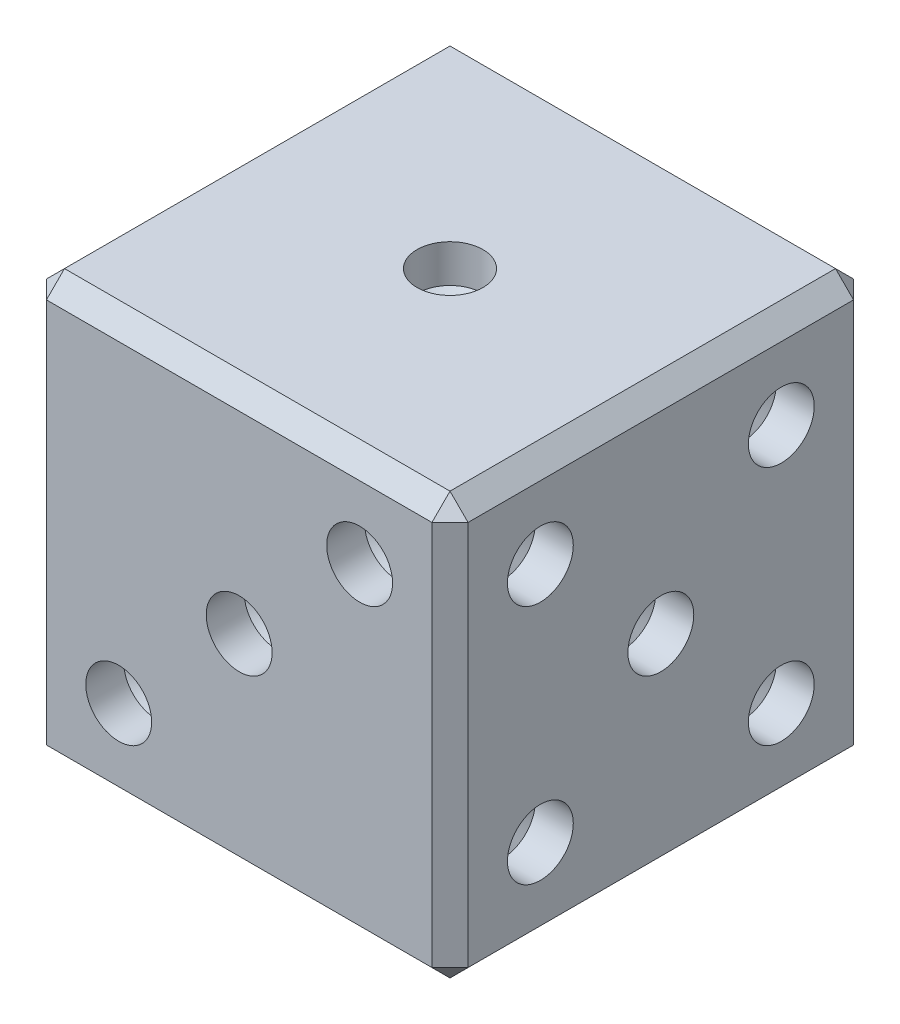
SolidWorks part; units mm, degrees
ref_plane "Front Plane" through (0, 0, 0) normal (0, 0, 1) x (1, 0, 0)
ref_plane "Top Plane" through (0, 0, 0) normal (0, 1, 0) x (1, 0, 0)
ref_plane "Right Plane" through (0, 0, 0) normal (1, 0, 0) x (0, 0, -1)
sketch "Sketch1" plane through (0, 0, 0) normal (0, 1, 0) x (1, 0, 0)
  line L1 (-8.89, -8.89) -> (8.89, -8.89)
  line L2 (-8.89, -8.89) -> (-8.89, 8.89)
  line L3 (-8.89, 8.89) -> (8.89, 8.89)
  line L4 (8.89, -8.89) -> (8.89, 8.89)
  line L5 (-8.89, -8.89) -> (8.89, 8.89) construction
  line L6 (-8.89, 8.89) -> (8.89, -8.89) construction
  point P0 (0, 0)
  dimension "D1" = 17.78
  dimension "D2" = 17.78
extrude "Boss-Extrude1" add sketch "Sketch1" along normal mid plane 17.78 contours L2 L1 L4 L3
sketch "Sketch2" plane through (0, 0, 0) normal (0, 0, 1) x (1, 0, 0)
  line L5 (-5.08, -5.08) -> (5.08, -5.08)
  line L6 (-5.08, -5.08) -> (-5.08, 5.08)
  line L7 (-5.08, 5.08) -> (5.08, 5.08)
  line L8 (5.08, -5.08) -> (5.08, 5.08)
  line L9 (-5.08, -5.08) -> (5.08, 5.08) construction
  line L10 (-5.08, 5.08) -> (5.08, -5.08) construction
  point P0 (0, 0)
  point P5 (0, 0)
  dimension "D1" = 10.16
  dimension "D2" = 10.16
sketch "Sketch3" plane through (0, 0, 0) normal (0, 1, 0) x (1, 0, 0)
  line L5 (-5.08, -5.08) -> (5.08, -5.08)
  line L6 (-5.08, -5.08) -> (-5.08, 5.08)
  line L7 (-5.08, 5.08) -> (5.08, 5.08)
  line L8 (5.08, -5.08) -> (5.08, 5.08)
  line L9 (-5.08, -5.08) -> (5.08, 5.08) construction
  line L10 (-5.08, 5.08) -> (5.08, -5.08) construction
  point P0 (0, 0)
  dimension "D1" = 10.16
  dimension "D2" = 10.16
sketch "Sketch4" plane through (0, 0, 0) normal (1, 0, 0) x (0, 0, -1)
  line L5 (-5.08, -5.08) -> (5.08, -5.08)
  line L6 (-5.08, -5.08) -> (-5.08, 5.08)
  line L7 (-5.08, 5.08) -> (5.08, 5.08)
  line L8 (5.08, -5.08) -> (5.08, 5.08)
  line L9 (-5.08, -5.08) -> (5.08, 5.08) construction
  line L10 (-5.08, 5.08) -> (5.08, -5.08) construction
  point P0 (0, 0)
  dimension "D1" = 10.16
  dimension "D2" = 10.16
chamfer "Chamfer1" distance 0.762 angle 45 12 edges at (-8.89, 0, -8.89) (0, 8.89, -8.89) (-8.89, 8.89, 0) (-8.89, 0, 8.89) (0, 8.89, 8.89) (8.89, 0, 8.89) (8.89, 8.89, 0) (8.89, 0, -8.89) (8.89, -8.89, 0) (0, -8.89, -8.89) (-8.89, -8.89, 0) (0, -8.89, 8.89)
hole_wizard "7/64 (0.10938) Diameter Hole1" positions "Sketch6" profile "Sketch5" hole size "7/64" standard "ANSI Inch"
sketch "Sketch6" plane through (0, 8.89, 0) normal (0, 1, 0) x (1, 0, 0)
  point P0 (0, 0)
sketch "Sketch5" plane through (0, 8.89, 0) normal (1, 0, 0) x (0, 0, 1)
  line L0 (0, 0) -> (0, 2.4349)
  line L1 (0, 2.4349) -> (1.3891, 1.6002)
  line L2 (1.3891, 1.6002) -> (1.3891, 0)
  line L5 (1.3891, 0) -> (0, 0)
  line L10 (0, 2.4349) -> (-1.3891, 1.6002) construction
  line L11 (0, -6.35) -> (0, 107.95) construction
  dimension "Hole Dia." = 2.7783
  dimension "Hole Depth" = 1.6002
  dimension "Drill Angle" = 118
hole_wizard "7/64 (0.10938) Diameter Hole2" positions "Sketch17" profile "Sketch18" hole size "7/64" standard "ANSI Inch"
sketch "Sketch17" plane through (0, -8.89, 0) normal (0, -1, 0) x (-1, 0, 0)
  line L0 (5.08, -5.08) -> (5.08, 5.08) construction
  line L1 (5.08, 0) -> (-5.08, 0) construction
  line L2 (5.08, 0) -> (-5.08, 0) construction
  line L3 (-5.08, -5.08) -> (-5.08, 5.08) construction
  point P0 (5.08, -5.08)
  point P3 (5.08, 0)
  point P7 (5.08, 5.08)
  point P10 (-5.08, 5.08)
  point P13 (-5.08, 0)
  point P19 (-5.08, -5.08)
  point P22 (-5.08, 0)
sketch "Sketch18" plane through (-5.08, -8.89, 5.08) normal (1, 0, 0) x (0, 0, -1)
  line L0 (0, 0) -> (0, 2.4349)
  line L1 (0, 2.4349) -> (1.3891, 1.6002)
  line L2 (1.3891, 1.6002) -> (1.3891, 0)
  line L5 (1.3891, 0) -> (0, 0)
  line L10 (0, 2.4349) -> (-1.3891, 1.6002) construction
  line L11 (0, -6.35) -> (0, 107.95) construction
  dimension "Hole Dia." = 2.7783
  dimension "Hole Depth" = 1.6002
  dimension "Drill Angle" = 118
hole_wizard "7/64 (0.10938) Diameter Hole3" positions "Sketch21" profile "Sketch22" hole size "7/64" standard "ANSI Inch"
sketch "Sketch21" plane through (0, 0, 8.89) normal (0, 0, 1) x (1, 0, 0)
  point P0 (-5.08, -5.08)
  point P3 (0, 0)
  point P6 (5.08, 5.08)
sketch "Sketch22" plane through (-5.08, -5.08, 8.89) normal (1, 0, 0) x (0, -1, 0)
  line L0 (0, 0) -> (0, 2.4349)
  line L1 (0, 2.4349) -> (1.3891, 1.6002)
  line L2 (1.3891, 1.6002) -> (1.3891, 0)
  line L5 (1.3891, 0) -> (0, 0)
  line L10 (0, 2.4349) -> (-1.3891, 1.6002) construction
  line L11 (0, -6.35) -> (0, 107.95) construction
  dimension "Hole Dia." = 2.7783
  dimension "Hole Depth" = 1.6002
  dimension "Drill Angle" = 118
hole_wizard "7/64 (0.10938) Diameter Hole5" positions "Sketch25" profile "Sketch26" hole size "7/64" standard "ANSI Inch"
sketch "Sketch25" plane through (-8.89, 0, 0) normal (-1, 0, 0) x (0, 0, 1)
  point P0 (-5.08, 5.08)
  point P3 (5.08, -5.08)
sketch "Sketch26" plane through (-8.89, 5.08, -5.08) normal (0, 1, 0) x (0, 0, 1)
  line L0 (0, 0) -> (0, 2.4349)
  line L1 (0, 2.4349) -> (1.3891, 1.6002)
  line L2 (1.3891, 1.6002) -> (1.3891, 0)
  line L5 (1.3891, 0) -> (0, 0)
  line L10 (0, 2.4349) -> (-1.3891, 1.6002) construction
  line L11 (0, -6.35) -> (0, 107.95) construction
  dimension "Hole Dia." = 2.7783
  dimension "Hole Depth" = 1.6002
  dimension "Drill Angle" = 118
hole_wizard "7/64 (0.10938) Diameter Hole6" positions "Sketch27" profile "Sketch28" hole size "7/64" standard "ANSI Inch"
sketch "Sketch27" plane through (8.89, 0, 0) normal (1, 0, 0) x (0, 0, -1)
  point P0 (-5.08, 5.08)
  point P3 (-5.08, -5.08)
  point P6 (5.08, -5.08)
  point P9 (5.08, 5.08)
  point P12 (0, 0)
sketch "Sketch28" plane through (8.89, 5.08, 5.08) normal (0, 1, 0) x (0, 0, -1)
  line L0 (0, 0) -> (0, 2.4349)
  line L1 (0, 2.4349) -> (1.3891, 1.6002)
  line L2 (1.3891, 1.6002) -> (1.3891, 0)
  line L5 (1.3891, 0) -> (0, 0)
  line L10 (0, 2.4349) -> (-1.3891, 1.6002) construction
  line L11 (0, -6.35) -> (0, 107.95) construction
  dimension "Hole Dia." = 2.7783
  dimension "Hole Depth" = 1.6002
  dimension "Drill Angle" = 118
hole_wizard "7/64 (0.10938) Diameter Hole7" positions "Sketch29" profile "Sketch30" hole size "7/64" standard "ANSI Inch"
sketch "Sketch29" plane through (0, 0, -8.89) normal (0, 0, -1) x (-1, 0, 0)
  point P0 (-5.08, 5.08)
  point P3 (-5.08, -5.08)
  point P6 (5.08, -5.08)
  point P9 (5.08, 5.08)
sketch "Sketch30" plane through (5.08, 5.08, -8.89) normal (1, 0, 0) x (0, 1, 0)
  line L0 (0, 0) -> (0, 2.4349)
  line L1 (0, 2.4349) -> (1.3891, 1.6002)
  line L2 (1.3891, 1.6002) -> (1.3891, 0)
  line L5 (1.3891, 0) -> (0, 0)
  line L10 (0, 2.4349) -> (-1.3891, 1.6002) construction
  line L11 (0, -6.35) -> (0, 107.95) construction
  dimension "Hole Dia." = 2.7783
  dimension "Hole Depth" = 1.6002
  dimension "Drill Angle" = 118
